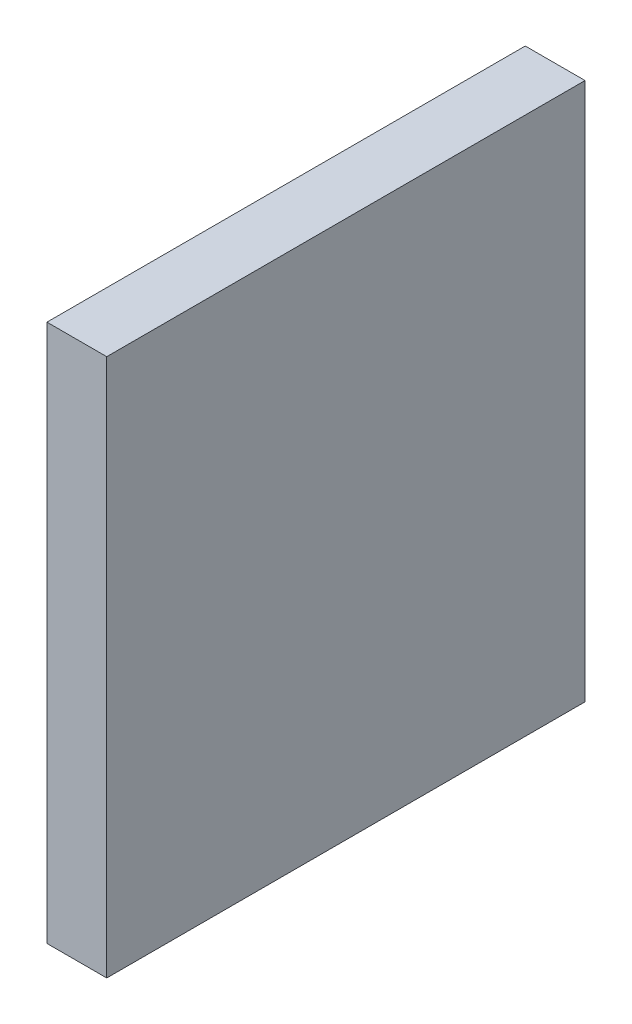
SolidWorks part; units mm, degrees
material "Teak"
ref_plane "Front Plane" through (0, 0, 0) normal (0, 0, 1) x (1, 0, 0)
ref_plane "Top Plane" through (0, 0, 0) normal (0, 1, 0) x (1, 0, 0)
ref_plane "Right Plane" through (0, 0, 0) normal (1, 0, 0) x (0, 0, -1)
sketch "Sketch1" plane through (0, 0, 0) normal (0, 1, 0) x (1, 0, 0)
  line L1 (0, 0) -> (12.7, 0)
  line L2 (0, 0) -> (0, 101.6)
  line L3 (0, 101.6) -> (12.7, 101.6)
  line L4 (12.7, 0) -> (12.7, 101.6)
  dimension "D1" = 12.7
  dimension "D2" = 101.6
extrude "Boss-Extrude1" add sketch "Sketch1" along normal blind 114.3
